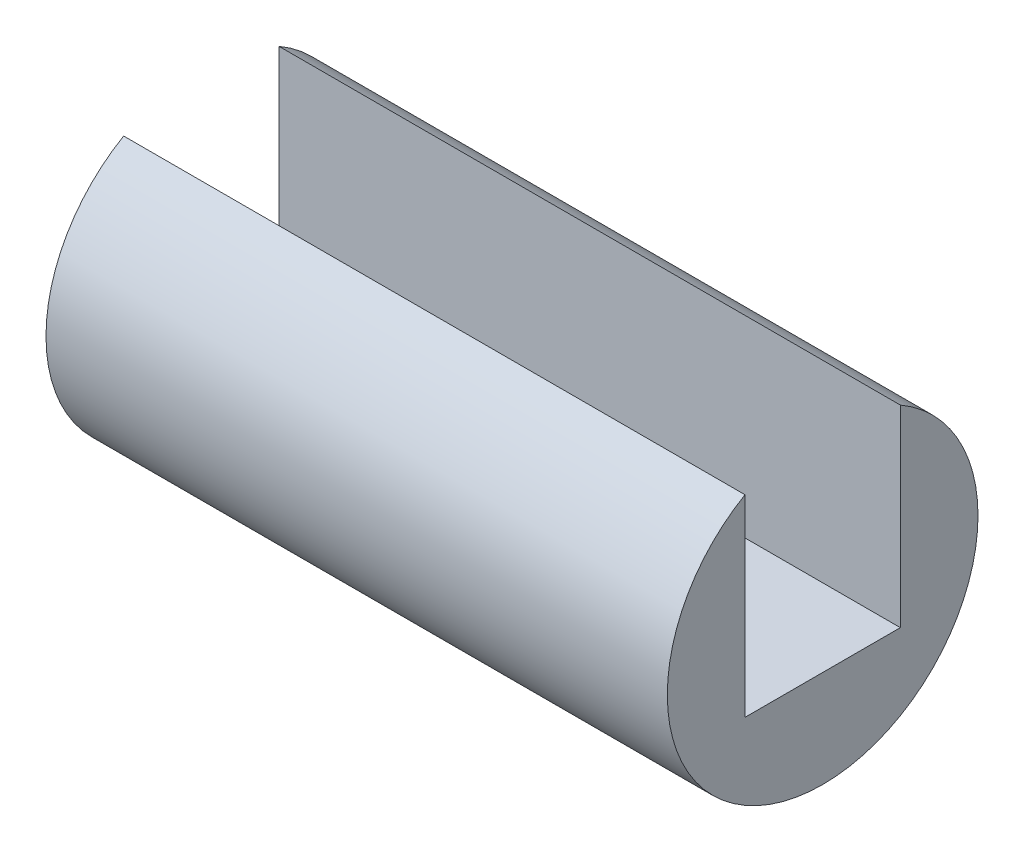
SolidWorks part; units mm, degrees
ref_plane "Front Plane" through (0, 0, 0) normal (0, 0, 1) x (1, 0, 0)
ref_plane "Top Plane" through (0, 0, 0) normal (0, 1, 0) x (1, 0, 0)
ref_plane "Right Plane" through (0, 0, 0) normal (1, 0, 0) x (0, 0, -1)
sketch "Sketch1" plane through (0, 0, 0) normal (1, 0, 0) x (0, 0, -1)
  line L2 (3.175, 2.3812) -> (-3.175, 2.3812)
  line L5 (0, -1.5875) -> (0, 11.1125) construction
  line L6 (-3.175, 11.1125) -> (3.175, 11.1125) construction
  line L7 (-3.175, 10.2618) -> (-3.175, 2.3812)
  line L8 (3.175, 10.2618) -> (3.175, 2.3812)
  arc A1 (3.175, 10.2618) -> (-3.175, 10.2618) centre (0, 4.7625) cw
  point P9 (0, 2.3812)
extrude "Boss-Extrude1" add sketch "Sketch1" along normal blind 25.4
